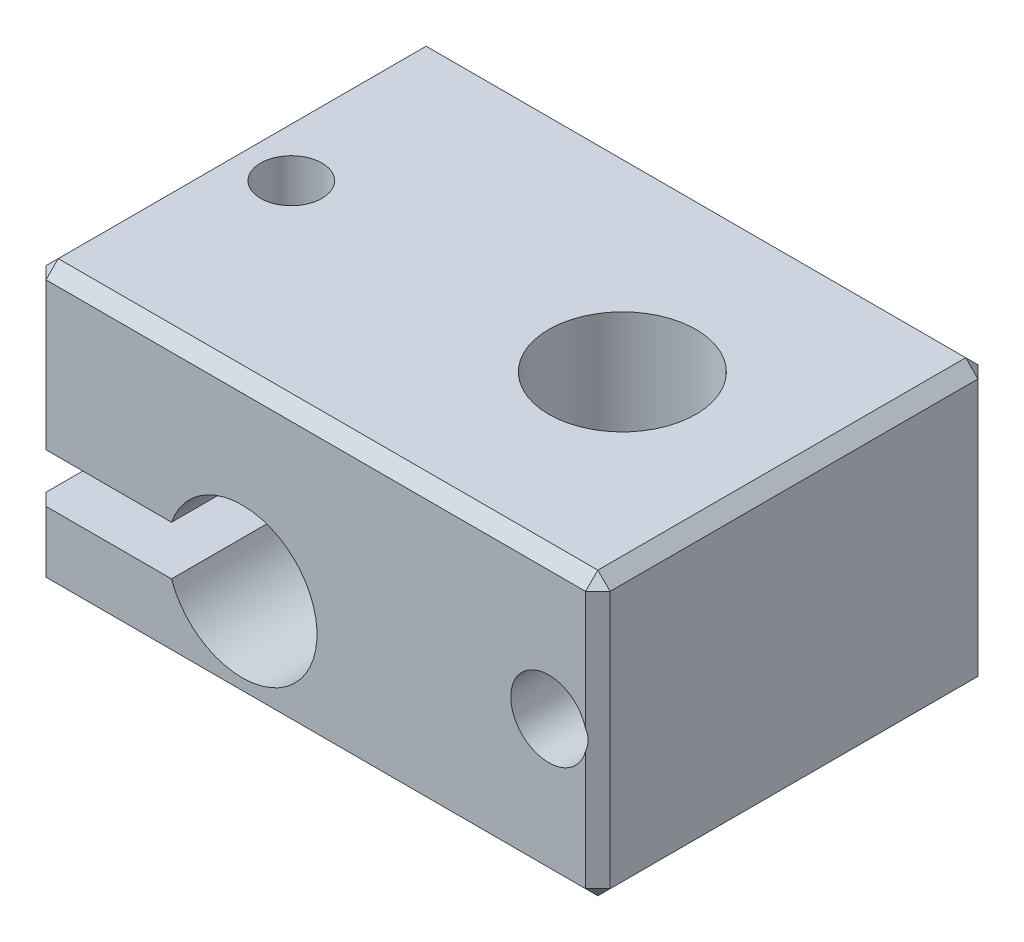
SolidWorks part; units mm, degrees
material "AISI 304"
ref_plane "Front Plane" through (0, 0, 0) normal (0, 0, 1) x (1, 0, 0)
ref_plane "Top Plane" through (0, 0, 0) normal (0, 1, 0) x (1, 0, 0)
ref_plane "Right Plane" through (0, 0, 0) normal (1, 0, 0) x (0, 0, -1)
sketch "Sketch1" plane through (0, 0, 0) normal (0, 0, 1) x (1, 0, 0)
  line L0 (-11.5, -0.75) -> (-5.8814, -0.75)
  line L1 (-11.5, -5.75) -> (11.5, -5.75)
  line L2 (-11.5, -5.75) -> (-11.5, 5.75) construction
  line L3 (-11.5, 5.75) -> (11.5, 5.75)
  line L4 (11.5, -5.75) -> (11.5, 5.75)
  line L5 (-11.5, -5.75) -> (11.5, 5.75) construction
  line L6 (-11.5, 5.75) -> (11.5, -5.75) construction
  line L7 (-5.8814, -2.75) -> (-11.5, -2.75)
  line L8 (-11.5, 5.75) -> (-11.5, -0.75)
  line L9 (-11.5, -2.75) -> (-11.5, -5.75)
  arc A0 (-5.8814, -0.75) -> (-5.8814, -2.75) centre (-3, -1.75) cw
  point P0 (0, 0)
  dimension "D3" = 4
  dimension "D5" = 3.05
  dimension "D1" = 23
  dimension "D2" = 11.5
  dimension "D4" = 2
  dimension "D6" = 8.5
extrude "Boss-Extrude1" add sketch "Sketch1" along normal mid plane 16
chamfer "Chamfer1" distance 0.5 angle 45 14 edges at (0, -5.75, -8) (-11.5, -4.25, -8) (-11.5, -5.75, 0) (-11.5, 2.5, -8) (-11.5, -4.25, 8) (0, -5.75, 8) (-11.5, 2.5, 8) (11.5, -5.75, 0) (11.5, 0, -8) (11.5, 0, 8) (11.5, 5.75, 0) (0, 5.75, -8) (0, 5.75, 8) (-11.5, 5.75, 0)
hole_wizard "M3x0.5 Tapped Hole1" [suppressed] positions "Sketch3" profile "Sketch2" tap size "M3x0.5" standard "ANSI Metric"
sketch "Sketch3" plane through (0, 0, 8) normal (0, 0, 1) x (1, 0, 0)
  line L0 (9.5, -5.75) -> (-9.5, -5.75) construction
  line L1 (10, 5.25) -> (10, -5.25) construction
  point P0 (6.5, -0.95)
  dimension "D1" = 4.8
  dimension "D2" = 3.5
sketch "Sketch2" plane through (6.5, -0.95, 8) normal (1, 0, 0) x (0, -1, 0)
  line L0 (0, 0) -> (0, 4.2511)
  line L1 (0, 4.2511) -> (1.25, 3.5)
  line L2 (1.25, 3.5) -> (1.25, 0)
  line L5 (1.25, 0) -> (0, 0)
  line L10 (0, 4.2511) -> (-1.25, 3.5) construction
  line L11 (0, -6.35) -> (0, 107.95) construction
  dimension "Tap Drill Dia." = 2.5
  dimension "Tap Drill Depth" = 3.5
  dimension "Drill Angle" = 118
cosmetic thread "Hole Thread2" [suppressed] parameters "D1"=3.5, "D2"=3
hole_wizard "Ø1.8 (1.8) Diameter Hole1" [suppressed] positions "Sketch5" profile "Sketch4" hole size "Ø1.8" standard "ANSI Metric"
sketch "Sketch5" plane through (0, 0, 8) normal (0, 0, 1) x (1, 0, 0)
  line L0 (9.5, -5.75) -> (-9.5, -5.75) construction
  line L1 (10, 5.25) -> (10, -5.25) construction
  point P0 (8, -3.75)
  dimension "D1" = 2
  dimension "D2" = 2
sketch "Sketch4" plane through (8, -3.75, 8) normal (1, 0, 0) x (0, -1, 0)
  line L0 (0, 0) -> (0, 2.5408)
  line L1 (0, 2.5408) -> (0.9, 2)
  line L2 (0.9, 2) -> (0.9, 0)
  line L5 (0.9, 0) -> (0, 0)
  line L10 (0, 2.5408) -> (-0.9, 2) construction
  line L11 (0, -6.35) -> (0, 107.95) construction
  dimension "Hole Dia." = 1.8
  dimension "Hole Depth" = 2
  dimension "Drill Angle" = 118
hole_wizard "Ø1.6 (1.6) Diameter Hole1" [suppressed] positions "Sketch7" profile "Sketch6" hole size "Ø1.6" standard "ANSI Metric"
sketch "Sketch7" [suppressed] plane through (0, 0, 8) normal (0, 0, 1) x (1, 0, 0)
  point P0 (8, -3.75)
sketch "Sketch6" plane through (8, -3.75, 8) normal (1, 0, 0) x (0, -1, 0)
  line L0 (0, 0) -> (0, 4.9807)
  line L1 (0, 4.9807) -> (0.8, 4.5)
  line L2 (0.8, 4.5) -> (0.8, 0)
  line L5 (0.8, 0) -> (0, 0)
  line L10 (0, 4.9807) -> (-0.8, 4.5) construction
  line L11 (0, -6.35) -> (0, 107.95) construction
  dimension "Hole Dia." = 1.6
  dimension "Hole Depth" = 4.5
  dimension "Drill Angle" = 118
hole_wizard "M3x0.5 Tapped Hole2" positions "Sketch9" profile "Sketch8" tap size "M3x0.5" standard "ANSI Metric" end condition through all
sketch "Sketch9" plane through (0, 5.75, 0) normal (0, 1, 0) x (1, 0, 0)
  line L1 (-11.5, -7.5) -> (-11.5, 7.5) construction
  point P0 (-9, 0)
  dimension "D1" = 2.5
sketch "Sketch8" plane through (-9, 5.75, 0) normal (1, 0, 0) x (0, 0, 1)
  line L0 (0, 0) -> (0, 11.5)
  line L1 (0, 11.5) -> (1.25, 11.5)
  line L2 (1.25, 11.5) -> (1.25, 0)
  line L5 (1.25, 0) -> (0, 0)
  line L11 (0, -6.35) -> (0, 107.95) construction
  dimension "Thread Major Dia." = 2.5
  dimension "Thru Tap Drill Depth" = 11.5
hole_wizard "M6x1.0 Tapped Hole1" positions "Sketch11" profile "Sketch12" tap size "M6x1.0" standard "ANSI Metric" end condition through all
sketch "Sketch11" plane through (0, 5.75, 0) normal (0, 1, 0) x (1, 0, 0)
  line L0 (-11.5, -7.5) -> (-11.5, 7.5) construction
  point P0 (4.5, 0)
  dimension "D1" = 16
sketch "Sketch12" plane through (4.5, 5.75, 0) normal (1, 0, 0) x (0, 0, 1)
  line L0 (0, 0) -> (0, 11.5)
  line L1 (0, 11.5) -> (3, 11.5)
  line L2 (3, 11.5) -> (3, 0)
  line L5 (3, 0) -> (0, 0)
  line L11 (0, -6.35) -> (0, 107.95) construction
  dimension "Thread Major Dia." = 6
  dimension "Thru Tap Drill Depth" = 11.5
hole_wizard "Ø3.1 (3.1) Diameter Hole1" positions "Sketch14" profile "Sketch13" hole size "Ø3.1" standard "ANSI Metric" end condition through all
sketch "Sketch14" plane through (0, 0, 8) normal (0, 0, 1) x (1, 0, 0)
  point P0 (9.5, 0)
  dimension "D1" = 9.5
sketch "Sketch13" plane through (9.5, 0, 8) normal (1, 0, 0) x (0, -1, 0)
  line L0 (0, 0) -> (0, 16)
  line L1 (0, 16) -> (1.55, 16)
  line L2 (1.55, 16) -> (1.55, 0)
  line L5 (1.55, 0) -> (0, 0)
  line L11 (0, -6.35) -> (0, 107.95) construction
  dimension "Thru Hole Dia." = 3.1
  dimension "Thru Hole Depth" = 16
hole_wizard "M3x0.5 Tapped Hole3" positions "Sketch16" profile "Sketch15" tap size "M3x0.5" standard "ANSI Metric"
sketch "Sketch16" plane through (0, -5.75, 0) normal (0, -1, 0) x (-1, 0, 0)
  point P0 (-9.5, 0)
  dimension "D1" = 9.5
sketch "Sketch15" plane through (9.5, -5.75, 0) normal (1, 0, 0) x (0, 0, -1)
  line L0 (0, 0) -> (0, 4.2)
  line L1 (0, 4.2) -> (1.25, 4.2)
  line L2 (1.25, 4.2) -> (1.25, 0)
  line L5 (1.25, 0) -> (0, 0)
  line L11 (0, -6.35) -> (0, 107.95) construction
  dimension "Thread Major Dia." = 2.5
  dimension "Thru Tap Drill Depth" = 4.2
